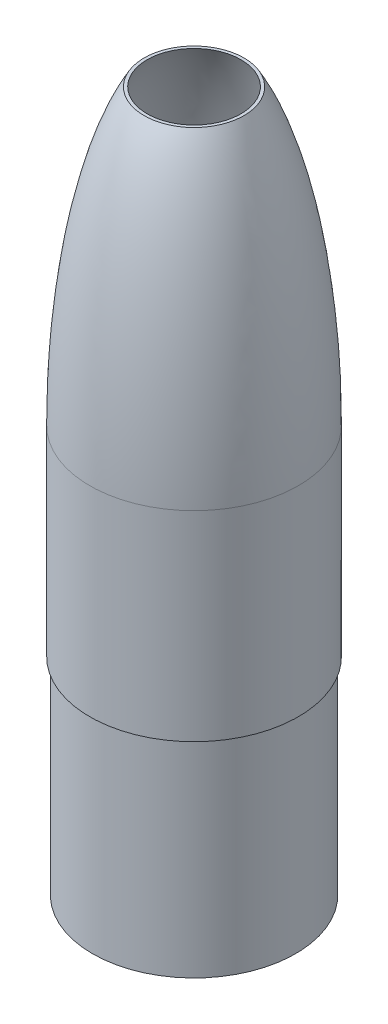
SolidWorks part; units mm, degrees
ref_plane "Front Plane" through (0, 0, 0) normal (0, 0, 1) x (1, 0, 0)
ref_plane "Top Plane" through (0, 0, 0) normal (0, 1, 0) x (1, 0, 0)
ref_plane "Right Plane" through (0, 0, 0) normal (1, 0, 0) x (0, 0, -1)
sketch "Sketch1" plane through (0, 0, 0) normal (0, 0, 1) x (1, 0, 0)
  line L9 (0, 0) -> (0, 654.6147) construction
  line L12 (76.2, 150) -> (76.2, 0)
  line L13 (78.16, 150) -> (78.16, 0)
  line L14 (0, 400) -> (0, 398.04)
  line L15 (76.2, 0) -> (78.16, 0)
  ellipse E0 centre (0, 150) end of major axis (0, 398.04) minor radius 76.2 (0, 398.04) -> (76.2, 150) cw
  spline S0 degree 1 poles (0, 400) (78.16, 150) knots 0 0 1 1 construction
  spline S1 degree 3 poles (0, 400) (2.7231, 400) (8.0954, 399.1311) (15.9852, 395.3134) (23.5507, 389.1306) (33.2071, 377.8754) (44.4036, 358.3688) (56.1093, 327.0871) (65.6898, 289.0807) (71.6144, 252.9938) (74.988, 222.2996) (76.8127, 198.5857) (77.9144, 174.416) (78.16, 158.1247) (78.16, 150) knots -1.570796 -1.570796 -1.570796 -1.570796 -1.472622 -1.374447 -1.276272 -1.178097 -0.981748 -0.785398 -0.589049 -0.392699 -0.294524 -0.19635 -0.098175 0 0 0 0
  point P7 (140, 150)
  point P8 (-133.3333, 150)
  point P9 (-4.7059, 391.1765)
  dimension "D4" = 76.2
  dimension "D2" = 150
  dimension "D3" = 76.2
  dimension "D5" = 1.96
revolve "Revolve1" add sketch "Sketch1" angle 360 about L9
ref_plane "Plane1" through (0, 150, 0) normal (0, 1, 0) x (1, 0, 0)
sketch "Sketch2" plane through (0, 150, 0) normal (0, 1, 0) x (1, 0, 0)
  circle A0 centre (0, 0) radius 76.2 construction
  circle A1 centre (0, 0) radius 76.2
  circle A2 centre (0, 0) radius 74.2
  dimension "D1" = 2
extrude "Boss-Extrude1" add sketch "Sketch2" against normal blind 304.8
ref_plane "Plane2" through (0, 400, 0) normal (0, -1, 0) x (-1, 0, 0)
sketch "Sketch3" plane through (0, 400, 0) normal (0, -1, 0) x (-1, 0, 0)
  circle A0 centre (0, 0) radius 102.134
extrude "Cut-Extrude1" cut sketch "Sketch3" along normal blind 30 contours A0
